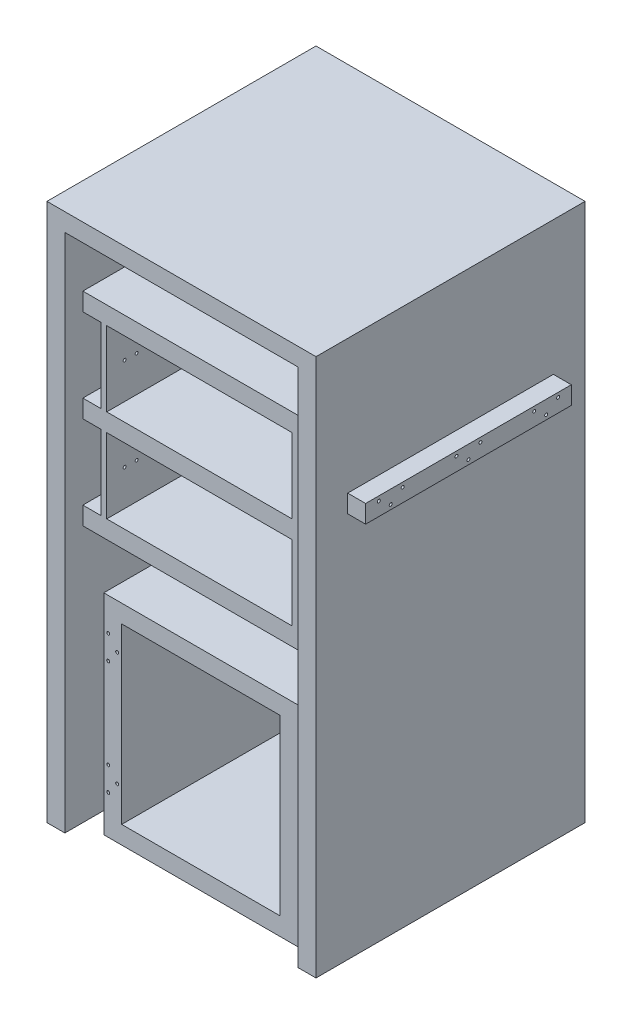
SolidWorks part; units mm, degrees
material "Teak"
ref_plane "Front Plane" through (0, 0, 0) normal (0, 0, 1) x (1, 0, 0)
ref_plane "Top Plane" through (0, 0, 0) normal (0, 1, 0) x (1, 0, 0)
ref_plane "Right Plane" through (0, 0, 0) normal (1, 0, 0) x (0, 0, -1)
sketch "Sketch1" plane through (0, 0, 0) normal (1, 0, 0) x (0, 0, -1)
  line L1 (225, -450) -> (-225, -450)
  line L2 (225, -450) -> (225, 450)
  line L3 (225, 450) -> (-225, 450)
  line L4 (-225, -450) -> (-225, 450)
  line L5 (225, -450) -> (-225, 450) construction
  line L6 (225, 450) -> (-225, -450) construction
  point P0 (0, 0)
  dimension "D1" = 450
  dimension "D2" = 900
extrude "Boss-Extrude1" add sketch "Sketch1" along normal mid plane 450
sketch "Sketch2" plane through (0, 0, 225) normal (0, 0, 1) x (1, 0, 0)
  line L0 (225, -450) -> (-225, -450) construction
  line L1 (-195, -450) -> (195, -450)
  line L2 (-195, -450) -> (-195, 420)
  line L3 (-195, 420) -> (195, 420)
  line L4 (195, -450) -> (195, 420)
  line L5 (225, 450) -> (-225, 450) construction
  line L6 (225, 450) -> (225, -450) construction
  line L7 (-225, 450) -> (-225, -450) construction
  dimension "D1" = 30
  dimension "D2" = 30
  dimension "D3" = 30
extrude "Cut-Extrude1" cut sketch "Sketch2" against normal blind 420
ref_plane "Plane1" through (0, 320, 0) normal (0, 1, 0) x (1, 0, 0)
sketch "Sketch3" plane through (0, 320, 0) normal (0, 1, 0) x (1, 0, 0)
  line L0 (195, 195) -> (195, -225) construction
  line L1 (-195, 195) -> (195, 195) construction
  line L2 (-195, 195) -> (-195, -225) construction
  line L3 (195, 195) -> (195, -195)
  line L4 (-195, 195) -> (195, 195)
  line L5 (-195, 195) -> (-195, -195)
  line L6 (-195, -195) -> (195, -195)
  line L8 (-195, -225) -> (-225, -225) construction
  dimension "D1" = 30
extrude "Boss-Extrude2" add sketch "Sketch3" against normal blind 30
pattern_linear "LPattern1" count 3 spacing 155 along (0, -1, 0) of "Boss-Extrude2"
ref_plane "Plane2" through (0, 150, 0) normal (0, 1, 0) x (1, 0, 0)
sketch "Sketch5" plane through (0, 0, -195) normal (0, 0, 1) x (1, 0, 0)
  line L0 (-195, -450) -> (195, -450) construction
  line L1 (-130, -129.5408) -> (135, -129.5408)
  line L2 (-160, -99.5408) -> (165, -99.5408)
  line L3 (-160, -450) -> (165, -450)
  line L5 (-160, -450) -> (-160, -99.5408)
  line L7 (165, -450) -> (165, -99.5408)
  line L11 (135, -420) -> (-130, -420)
  line L12 (135, -420) -> (135, -129.5408)
  line L14 (-130, -420) -> (-130, -129.5408)
  line L17 (195, -450) -> (195, 420) construction
  line L18 (-195, 420) -> (-195, -450) construction
  point P6 (2.5, -250)
  point P11 (0, -235)
  dimension "D2" = 30
  dimension "D3" = 35
  dimension "D4" = 30
  dimension "D6" = 30
extrude "Boss-Extrude4" add sketch "Sketch5" along normal blind 390
ref_plane "Plane3" through (-165, 0, 0) normal (1, 0, 0) x (0, 0, -1)
sketch "Sketch6" plane through (-165, 0, 0) normal (1, 0, 0) x (0, 0, -1)
  line L1 (-195, 290) -> (195, 290) construction
  line L2 (-195, 165) -> (195, 165)
  line L3 (-195, 290) -> (-195, 165)
  line L4 (-195, 290) -> (195, 290)
  line L6 (195, 165) -> (195, 290)
  line L7 (195, 165) -> (195, 290) construction
extrude "Boss-Extrude5" add sketch "Sketch6" along normal blind 10
pattern_linear "LPattern2" count 2 spacing 155 along (0, -1, 0) count 2 spacing 320 along (1, 0, 0) of "Boss-Extrude5"
sketch "Sketch10" plane through (-155, 0, 0) normal (1, 0, 0) x (0, 0, -1)
  line L0 (-195, 225) -> (195, 225) construction
  line L1 (-195, 290) -> (-195, 165) construction
  line L3 (195, 320) -> (-195, 320) construction
  line L4 (0, 225) -> (0, 290) construction
  line L8 (195, 165) -> (195, 290)
  line L9 (195, 290) -> (-195, 290)
  line L10 (-195, 290) -> (-195, 165)
  line L11 (-195, 165) -> (195, 165)
  line L12 (195, 165) -> (195, 290) construction
  line L13 (195, 290) -> (-195, 290) construction
  line L14 (-195, 290) -> (-195, 165) construction
  line L15 (-195, 165) -> (195, 165) construction
  circle A0 centre (-165, 225) radius 2.5
  circle A1 centre (-145, 225) radius 2.5
  circle A2 centre (145, 225) radius 2.5
  circle A3 centre (165, 225) radius 2.5
  dimension "D3" = 5
  dimension "D1" = 95
  dimension "D4" = 20
  dimension "D5" = 30
  dimension "D2" = 0
extrude "Cut-Extrude2" cut sketch "Sketch10" against normal up to next contours A0
pattern_linear "LPattern3" count 2 spacing 155 along (0, -1, 0) count 2 spacing 320 along (1, 0, 0) of "Cut-Extrude2"
sketch "Sketch13" plane through (225, 0, 0) normal (1, 0, 0) x (0, 0, -1)
  line L0 (-225, 450) -> (-225, -450) construction
  line L1 (-225, 225.86) -> (225, 225.86)
  line L2 (-225, 225.86) -> (-225, 195.86)
  line L3 (-225, 195.86) -> (225, 195.86)
  line L4 (225, 225.86) -> (225, 195.86)
  line L5 (225, -450) -> (225, 450) construction
  line L6 (225, 450) -> (-225, 450) construction
  dimension "D1" = 224.14
  dimension "D2" = 30
extrude "Boss-Extrude6" add sketch "Sketch13" along normal blind 30
sketch "Sketch12" plane through (225, 0, 0) normal (1, 0, 0) x (0, 0, -1)
  line L0 (-225, 218.36) -> (225, 218.36) construction
  line L1 (-225, 450) -> (-225, 225.86) construction
  line L2 (225, -450) -> (225, 195.86) construction
  line L4 (0, 218.36) -> (0, 0) construction
  line L5 (225, 450) -> (-225, 450) construction
  circle A0 centre (-150, 218.36) radius 2.5
  circle A1 centre (-110, 218.36) radius 2.5
  circle A2 centre (-130, 203.36) radius 2.5
  circle A3 centre (110, 218.36) radius 2.5
  circle A4 centre (130, 203.36) radius 2.5
  circle A5 centre (150, 218.36) radius 2.5
  dimension "D6" = 5
  dimension "D1" = 231.64
  dimension "D2" = 75
  dimension "D3" = 40
  dimension "D4" = 20
  dimension "D5" = 15
extrude "Cut-Extrude4" cut sketch "Sketch12" along normal up to next
ref_plane "Plane4" through (0, -269.7708, 0) normal (0, 1, 0) x (1, 0, 0)
sketch "Sketch17" plane through (0, 0, 195) normal (0, 0, 1) x (1, 0, 0)
  line L0 (178.75, -269.7708) -> (-178.75, -269.7708) construction
  line L1 (-152.5, -269.7708) -> (-122.5, -269.7708)
  line L7 (-152.5, -269.7708) -> (-122.5, -269.7708)
  line L11 (-137.5, -269.7708) -> (-99.8855, -269.7708)
  circle A0 centre (-152.5, -194.5408) radius 2.5
  circle A1 centre (-152.5, -154.5408) radius 2.5
  circle A2 centre (-137.5, -174.5408) radius 2.5
  dimension "D3" = 5
  dimension "D5" = 5
  dimension "D8" = 5
extrude "Cut-Extrude5" cut sketch "Sketch17" against normal blind 10 and the other way through all contours A0 | A2 | A1
mirror "Mirror1" about plane through (0, -269.7708, 0) normal (0, 1, 0) of "Cut-Extrude5"
sketch "Sketch18" plane through (225, 0, 0) normal (1, 0, 0) x (0, 0, -1)
  line L0 (-225, 195.86) -> (225, 195.86) construction
  line L1 (-225, 225.86) -> (-172, 225.86)
  line L2 (-225, 225.86) -> (-225, 195.86)
  line L3 (-225, 195.86) -> (-172, 195.86)
  line L4 (-172, 225.86) -> (-172, 195.86)
  dimension "D1" = 53
extrude "Cut-Extrude6" cut sketch "Sketch18" along normal through all
sketch "Sketch19" plane through (255, 0, 0) normal (1, 0, 0) x (0, 0, -1)
  line L0 (-172, 195.86) -> (225, 195.86) construction
  line L1 (225, 225.86) -> (172, 225.86)
  line L2 (225, 225.86) -> (225, 195.86)
  line L3 (225, 195.86) -> (172, 195.86)
  line L4 (172, 225.86) -> (172, 195.86)
  dimension "D1" = 53
extrude "Cut-Extrude7" cut sketch "Sketch19" against normal blind 30
sketch "Sketch20" plane through (255, 0, 0) normal (1, 0, 0) x (0, 0, -1)
  circle A0 centre (-20, 218.36) radius 2.5
  circle A1 centre (0, 203.36) radius 2.5
  circle A2 centre (20, 218.36) radius 2.5
  dimension "D1" = 5
  dimension "D2" = 5
  dimension "D3" = 5
extrude "Cut-Extrude8" cut sketch "Sketch20" against normal blind 10
